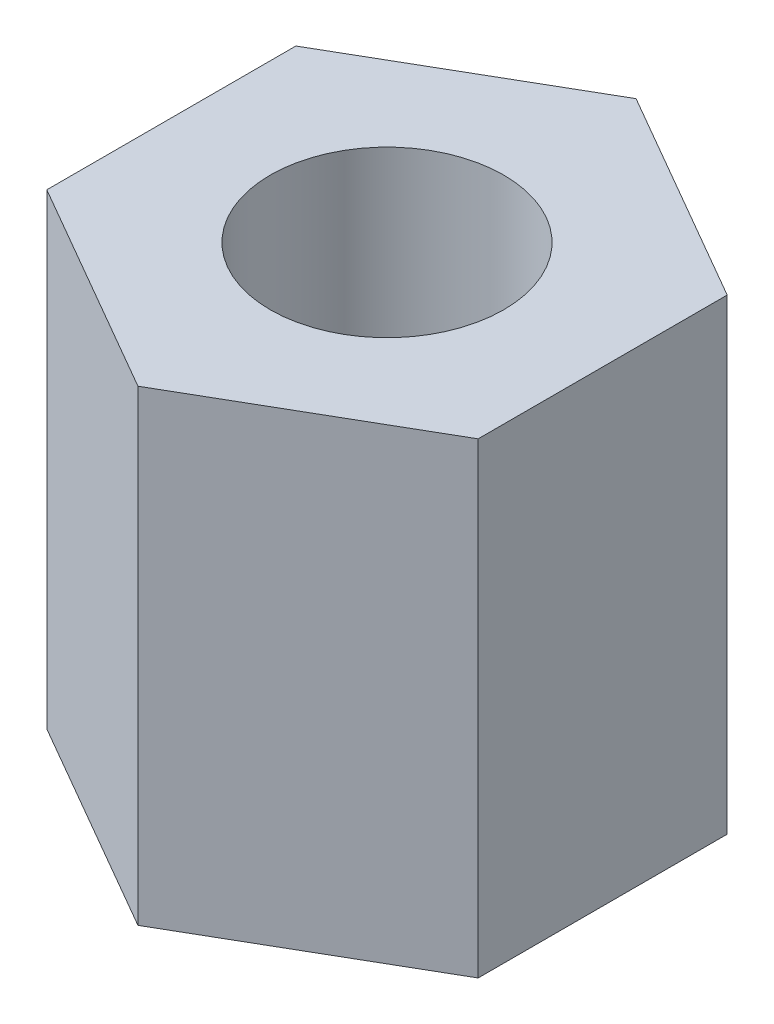
SolidWorks part; units mm, degrees
ref_plane "Front Plane" through (0, 0, 0) normal (0, 0, 1) x (1, 0, 0)
ref_plane "Top Plane" through (0, 0, 0) normal (0, 1, 0) x (1, 0, 0)
ref_plane "Right Plane" through (0, 0, 0) normal (1, 0, 0) x (0, 0, -1)
sketch "Sketch1" plane through (0, 0, 0) normal (0, 1, 0) x (1, 0, 0)
  line L1 (0, 8) -> (-6.9282, 4)
  line L2 (-6.9282, 4) -> (-6.9282, -4)
  line L3 (-6.9282, -4) -> (0, -8)
  line L4 (0, -8) -> (6.9282, -4)
  line L5 (6.9282, -4) -> (6.9282, 4)
  line L6 (6.9282, 4) -> (0, 8)
  circle A0 centre (0, 0) radius 5 construction
  circle A3 centre (0, 0) radius 3.75
  circle A4 centre (0, 0) radius 8 construction
  dimension "D1" = 7.5
  dimension "D2" = 16
extrude "Boss-Extrude1" add sketch "Sketch1" along normal blind 15
